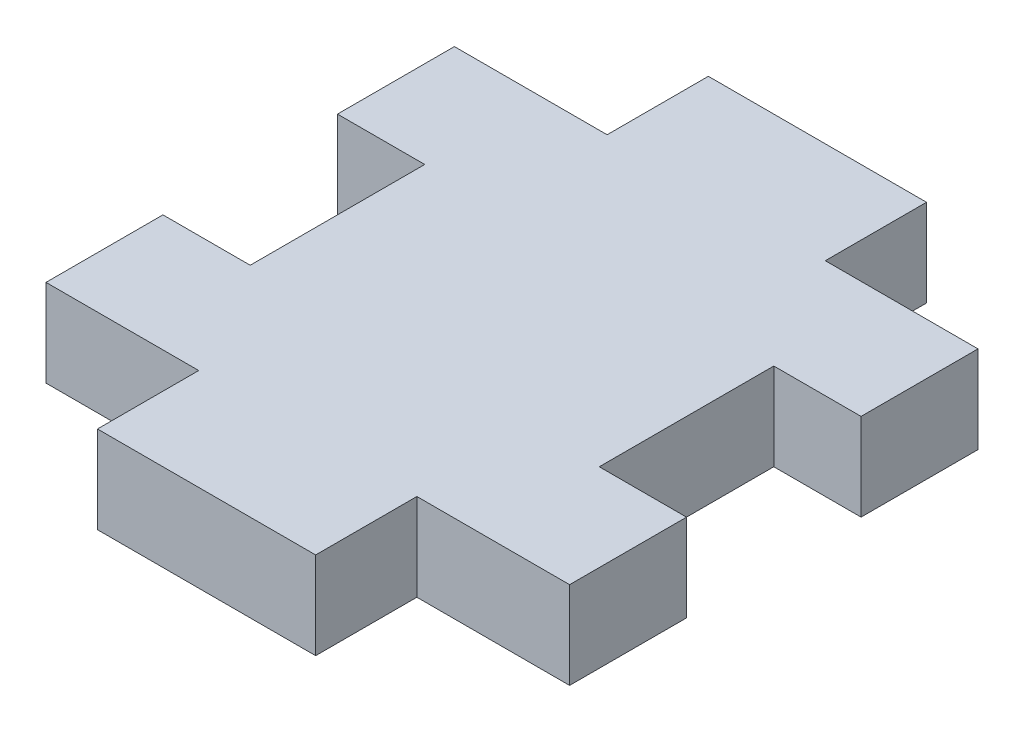
SolidWorks part; units mm, degrees
material "Acrylic (Medium-high impact)"
ref_plane "Front Plane" through (0, 0, 0) normal (0, 0, 1) x (1, 0, 0)
ref_plane "Top Plane" through (0, 0, 0) normal (0, 1, 0) x (1, 0, 0)
ref_plane "Right Plane" through (0, 0, 0) normal (1, 0, 0) x (0, 0, -1)
sketch "Sketch1" plane through (0, 0, 0) normal (0, 1, 0) x (1, 0, 0)
  line L0 (-15.875, -29.718) -> (-38.1, -29.718)
  line L1 (15.875, -44.45) -> (-15.875, -44.45)
  line L2 (15.875, -44.45) -> (15.875, -29.718)
  line L3 (15.875, 44.45) -> (-15.875, 44.45)
  line L4 (-15.875, -44.45) -> (-15.875, -29.718)
  line L5 (-15.875, 29.718) -> (-15.875, 44.45)
  line L6 (-15.875, 29.718) -> (-38.1, 29.718)
  line L7 (38.1, -29.718) -> (15.875, -29.718)
  line L8 (38.1, -29.718) -> (38.1, -12.7)
  line L9 (38.1, 29.718) -> (15.875, 29.718)
  line L10 (-38.1, -29.718) -> (-38.1, -12.7)
  line L11 (15.875, 29.718) -> (15.875, 44.45)
  line L12 (38.1, -12.7) -> (25.4, -12.7)
  line L13 (25.4, -12.7) -> (25.4, 12.7)
  line L14 (25.4, 12.7) -> (38.1, 12.7)
  line L15 (0, 0) -> (0, 11.5723) construction
  line L16 (-38.1, -12.7) -> (-25.4, -12.7)
  line L17 (-25.4, -12.7) -> (-25.4, 12.7)
  line L18 (-25.4, 12.7) -> (-38.1, 12.7)
  line L19 (-38.1, 12.7) -> (-38.1, 29.718)
  line L20 (38.1, 12.7) -> (38.1, 29.718)
  point P0 (0, 0)
  point P6 (0, 0)
  point P15 (0, 44.45)
  point P19 (25.4, 0)
  dimension "D1" = 31.75
  dimension "D3" = 76.2
  dimension "D5" = 14.732
  dimension "D2" = 14.732
  dimension "D4" = 88.9
  dimension "D6" = 25.4
  dimension "D7" = 12.7
extrude "Boss-Extrude1" add sketch "Sketch1" along normal blind 12.7
equation "\"D5@Sketch1\"=\"D2@Sketch1\""
